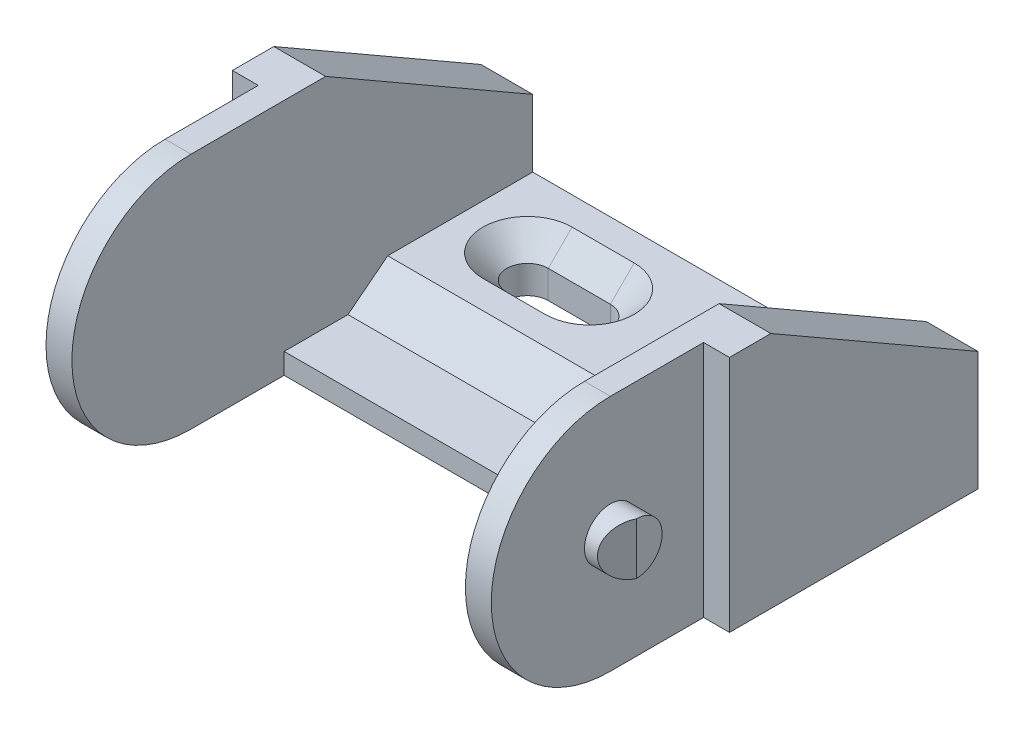
SolidWorks part; units mm, degrees
ref_plane "Front Plane" through (0, 0, 0) normal (0, 0, 1) x (1, 0, 0)
ref_plane "Top Plane" through (0, 0, 0) normal (0, 1, 0) x (1, 0, 0)
ref_plane "Right Plane" through (0, 0, 0) normal (1, 0, 0) x (0, 0, -1)
sketch "Sketch1" plane through (0, 0, 0) normal (1, 0, 0) x (0, 0, -1)
  line L0 (-16.5, 11.5) -> (-16.5, -11.5) construction
  line L1 (16.5, -11.5) -> (-16.5, -11.5)
  line L2 (16.5, -11.5) -> (16.5, 11.5)
  line L3 (16.5, 11.5) -> (-16.5, 11.5)
  line L5 (-16.5, 11.5) -> (16.5, -11.5) construction
  arc A1 (-16.5, 11.5) -> (-16.5, -11.5) centre (-16.5, 0) ccw
  point P0 (0, 0)
  dimension "D1" = 33
  dimension "D3" = 23
extrude "Boss-Extrude1" add sketch "Sketch1" along normal mid plane 48
sketch "Sketch2" plane through (24, 0, 0) normal (1, 0, 0) x (0, 0, -1)
  line L0 (16.5, 0) -> (-3.5, 11.5)
  line L1 (16.5, -11.5) -> (16.5, 11.5) construction
  line L2 (16.5, 11.5) -> (-16.5, 11.5) construction
  line L3 (-3.5, 11.5) -> (16.5, 11.5)
  line L4 (16.5, 11.5) -> (16.5, 0)
  dimension "D1" = 20
extrude "Cut-Extrude1" cut sketch "Sketch2" against normal blind 48
sketch "Sketch4" plane through (0, 0, 0) normal (1, 0, 0) x (0, 0, -1)
  line L0 (16.5, -11.5) -> (16.5, 0) construction
  line L1 (-3.5, 11.5) -> (16.5, 0) construction
  line L2 (-3.5, 11.5) -> (-16.5, 11.5) construction
  line L5 (16.5, -6.5) -> (16.5, 0)
  line L6 (-3.5, 11.5) -> (16.5, 0)
  line L7 (-3.5, 11.5) -> (-16.5, 11.5)
  line L10 (16.5, -6.5) -> (2.5, -6.5)
  line L11 (2.5, -6.5) -> (-1.3398, -9.5)
  line L12 (-1.3398, -9.5) -> (-7.5, -9.5)
  line L13 (-7.5, -9.5) -> (-7.5, -11.5)
  line L14 (-16.5, -11.5) -> (16.5, -11.5) construction
  line L15 (-16.5, -11.5) -> (-7.5, -11.5)
  arc A2 (-16.5, 11.5) -> (-16.5, -11.5) centre (-16.5, 0) ccw construction
  arc A3 (-16.5, 11.5) -> (-16.5, -11.5) centre (-16.5, 0) ccw
  dimension "D1" = 5
  dimension "D2" = 14
  dimension "D3" = 38
  dimension "D4" = 24
  dimension "D5" = 2
extrude "Cut-Extrude2" cut sketch "Sketch4" against normal mid plane 38
sketch "Sketch5" plane through (0, -6.5, 0) normal (0, 1, 0) x (1, 0, 0)
  line L0 (6.5, 9.5) -> (12.5, 9.5) construction
  line L1 (6.5, 11.5) -> (12.5, 11.5)
  line L2 (6.5, 7.5) -> (12.5, 7.5)
  line L3 (12.5, 9.5) -> (19, 9.5) construction
  line L4 (19, 2.5) -> (19, 16.5) construction
  arc A0 (6.5, 11.5) -> (6.5, 7.5) centre (6.5, 9.5) ccw
  arc A1 (12.5, 7.5) -> (12.5, 11.5) centre (12.5, 9.5) ccw
  point P2 (9.5, 9.5)
  dimension "D1" = 4
  dimension "D2" = 6
  dimension "D3" = 9.5
extrude "Cut-Extrude3" cut sketch "Sketch5" against normal through all
chamfer "Chamfer1" distance 2.3 angle 45 4 edges at (9.5, -6.5, -7.5) (14.5, -6.5, -9.5) (4.5, -6.5, -9.5) (9.5, -6.5, -11.5)
sketch "Sketch6" plane through (24, 0, 0) normal (1, 0, 0) x (0, 0, -1)
  line L0 (-3.5, 11.5) -> (-16.5, 11.5) construction
  line L1 (-7.5, 11.5) -> (-28, 11.5)
  line L2 (-7.5, 11.5) -> (-7.5, -11.5)
  line L3 (-7.5, -11.5) -> (-28, -11.5)
  line L4 (-28, 11.5) -> (-28, -11.5)
  line L5 (-16.5, -11.5) -> (16.5, -11.5) construction
  arc A0 (-16.5, 11.5) -> (-16.5, -11.5) centre (-16.5, 0) ccw construction
  dimension "D1" = 4
extrude "Cut-Extrude4" cut sketch "Sketch6" against normal blind 2.5
sketch "Sketch7" plane through (21.5, 0, 0) normal (1, 0, 0) x (0, 0, -1)
  circle A0 centre (-16.5, 0) radius 2.5
  dimension "D1" = 5
extrude "Boss-Extrude2" add sketch "Sketch7" along normal blind 2.5
sketch "Sketch8" plane through (0, 11.5, 0) normal (0, 1, 0) x (1, 0, 0)
  line L0 (24, -16.5) -> (22.75, -19)
  line L1 (24, -19) -> (24, -14) construction
  line L2 (21.5, -19) -> (24, -19) construction
  line L3 (22.75, -19) -> (24, -19)
  line L4 (24, -19) -> (24, -16.5)
extrude "Cut-Extrude5" cut sketch "Sketch8" against normal through all
mirror "Mirror1" about plane through (0, 0, 0) normal (1, 0, 0) of "Cut-Extrude3", "Chamfer1", "Cut-Extrude4", "Boss-Extrude2"
